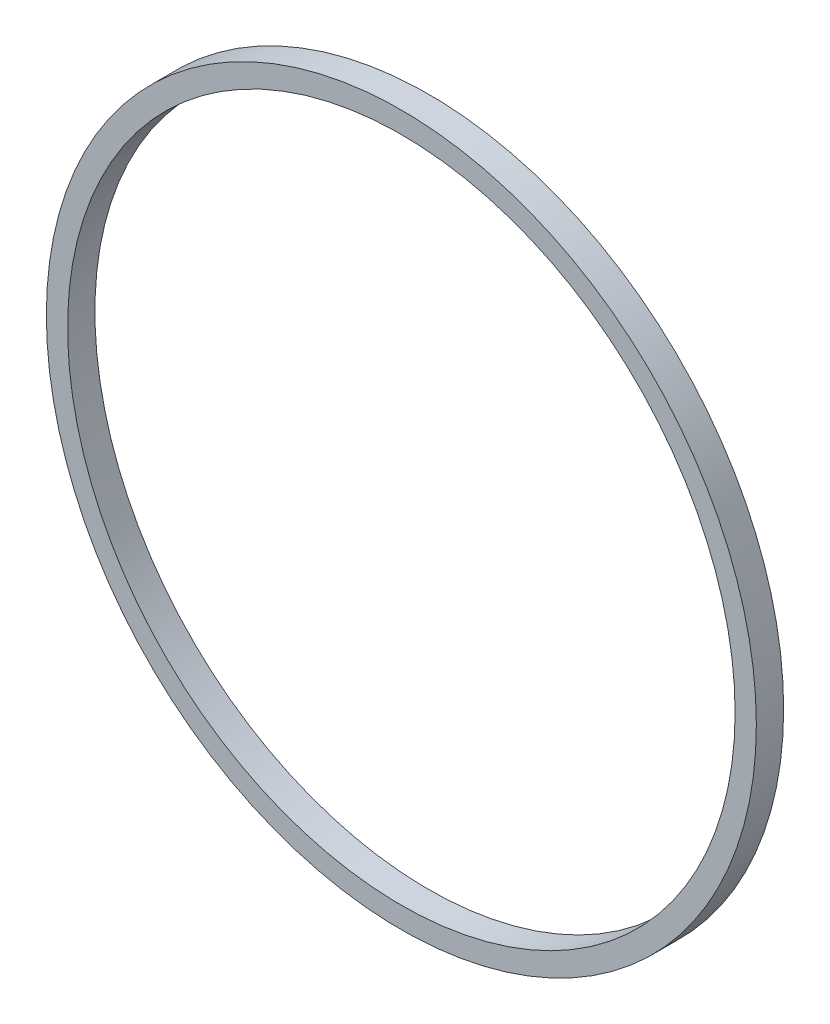
SolidWorks part; units mm, degrees
ref_plane "Front Plane" through (0, 0, 0) normal (0, 0, 1) x (1, 0, 0)
ref_plane "Top Plane" through (0, 0, 0) normal (0, 1, 0) x (1, 0, 0)
ref_plane "Right Plane" through (0, 0, 0) normal (1, 0, 0) x (0, 0, -1)
sketch "Sketch1" plane through (0, 0, 0) normal (0, 0, 1) x (1, 0, 0)
  arc B0 (164.1468, 89.4159) -> (164.1468, 79.1202) centre (165.1773, 84.268) ccw
  arc B1 (164.1468, 89.4159) -> (27.5816, 168.2619) centre (16.0718, -9.3656) ccw
  arc B2 (18.6652, 163.114) -> (27.5816, 168.2619) centre (22.6081, 166.5804) ccw
  arc B3 (18.6652, 163.114) -> (18.6652, 5.4221) centre (178.25, 84.268) ccw
  arc B4 (27.5816, 0.2742) -> (18.6652, 5.4221) centre (22.6081, 1.9557) ccw
  arc B5 (27.5816, 0.2742) -> (164.1468, 79.1202) centre (16.0718, 177.9017) ccw
  arc B6 (18.6136, 163.5731) -> (18.6136, 4.963) centre (178.25, 84.268) ccw
  arc B7 (27.2098, 0) -> (164.5701, 79.305) centre (16.0718, 177.9017) ccw
  arc B8 (164.5701, 89.231) -> (27.2098, 168.5361) centre (16.0718, -9.3656) ccw
  circle B9 centre (70.1312, 84.268) radius 63
  circle B10 centre (70.1312, 84.268) radius 59.5
  circle B11 centre (70.1312, 84.268) radius 58.5
  circle B12 centre (70.1312, 84.268) radius 55
sketch_block_instance "Seals Block-1"
sketch_block "Seals Block"
extrude "Boss-Extrude1" add sketch "Sketch1" along normal blind 4.5 contours B11 B12
